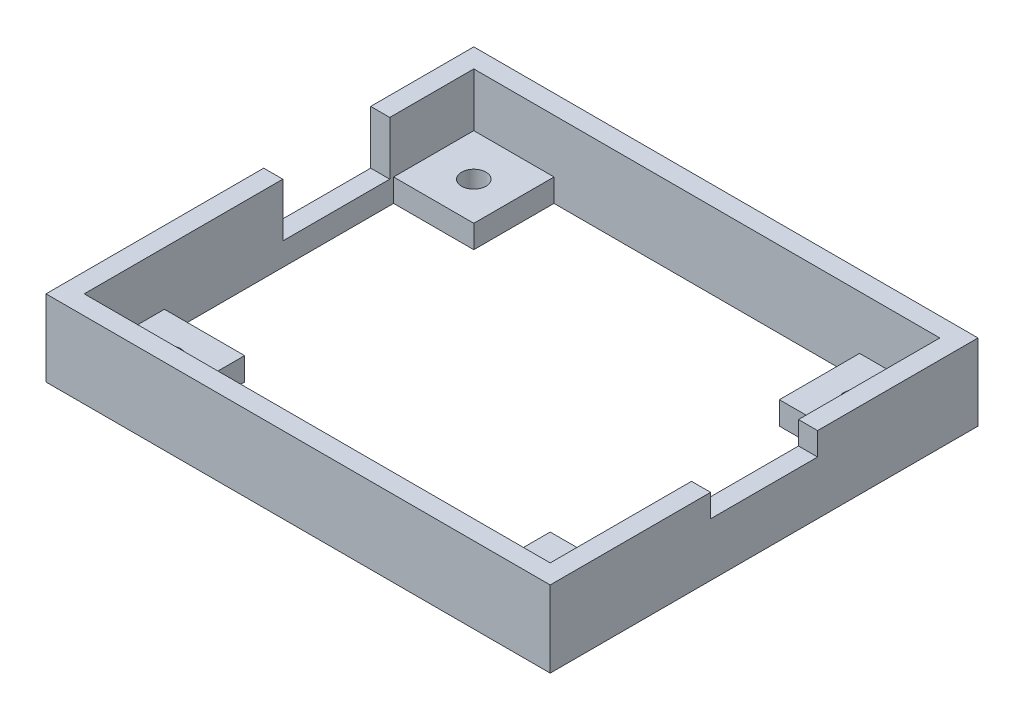
SolidWorks part; units mm, degrees
ref_plane "前视基准面" through (0, 0, 0) normal (0, 0, 1) x (1, 0, 0)
ref_plane "上视基准面" through (0, 0, 0) normal (0, 1, 0) x (1, 0, 0)
ref_plane "右视基准面" through (0, 0, 0) normal (1, 0, 0) x (0, 0, -1)
sketch "草图1" plane through (0, 0, 0) normal (0, 1, 0) x (1, 0, 0)
  line L1 (33, -28) -> (-33, -28)
  line L2 (33, -28) -> (33, 28)
  line L3 (33, 28) -> (-33, 28)
  line L4 (-33, -28) -> (-33, 28)
  line L5 (33, -28) -> (-33, 28) construction
  line L6 (33, 28) -> (-33, -28) construction
  point P0 (0, 0)
  dimension "D1" = 66
  dimension "D2" = 56
extrude "凸台-拉伸1" add sketch "草图1" along normal blind 10
sketch "草图2" plane through (0, 10, 0) normal (0, 1, 0) x (1, 0, 0)
  line L1 (30.5, -25.5) -> (-30.5, -25.5)
  line L2 (30.5, -25.5) -> (30.5, 25.5)
  line L3 (30.5, 25.5) -> (-30.5, 25.5)
  line L4 (-30.5, -25.5) -> (-30.5, 25.5)
  line L5 (30.5, -25.5) -> (-30.5, 25.5) construction
  line L6 (30.5, 25.5) -> (-30.5, -25.5) construction
  point P0 (0, 0)
  dimension "D1" = 61
  dimension "D2" = 51
extrude "切除-拉伸1" cut sketch "草图2" against normal blind 7
sketch "草图3" plane through (0, 3, 0) normal (0, 1, 0) x (1, 0, 0)
  line L1 (25, -20) -> (-25, -20) construction
  line L2 (25, -20) -> (25, 20) construction
  line L3 (25, 20) -> (-25, 20) construction
  line L4 (-25, -20) -> (-25, 20) construction
  line L5 (25, -20) -> (-25, 20) construction
  line L6 (25, 20) -> (-25, -20) construction
  circle A0 centre (-25, 20) radius 1.6
  point P0 (0, 0)
  dimension "D3" = 3.2
  dimension "D1" = 50
  dimension "D2" = 40
extrude "切除-拉伸2" cut sketch "草图3" against normal through all
pattern_linear "阵列(线性)1" count 2 spacing 50 along (1, 0, 0) count 2 spacing 40 along (0, 0, 1) of "切除-拉伸2"
sketch "草图4" plane through (0, 3, 0) normal (0, 1, 0) x (1, 0, 0)
  line L0 (-30.5, 25.5) -> (-30.5, -25.5) construction
  line L1 (30.5, -15) -> (-30.5, -15)
  line L2 (30.5, -15) -> (30.5, 15)
  line L3 (30.5, 15) -> (-30.5, 15)
  line L4 (-30.5, -15) -> (-30.5, 15)
  line L5 (30.5, -15) -> (-30.5, 15) construction
  line L6 (30.5, 15) -> (-30.5, -15) construction
  line L7 (30.5, 25.5) -> (-30.5, 25.5) construction
  line L8 (20, -25.5) -> (-20, -25.5)
  line L9 (20, -25.5) -> (20, 25.5)
  line L10 (20, 25.5) -> (-20, 25.5)
  line L11 (-20, -25.5) -> (-20, 25.5)
  line L12 (20, -25.5) -> (-20, 25.5) construction
  line L13 (20, 25.5) -> (-20, -25.5) construction
  point P0 (0, 0)
  point P8 (0, 0)
  line M8 (-30.5, 25.5) -> (-30.5, -25.5)
  line M9 (-30.5, -25.5) -> (30.5, -25.5)
  line M10 (30.5, -25.5) -> (30.5, 25.5)
  line M11 (30.5, 25.5) -> (-30.5, 25.5)
  dimension "D1" = 30
  dimension "D2" = 40
extrude "切除-拉伸3" cut sketch "草图4" against normal through all contours L11 L3 L9 M11 | L1 L11 L3 M8 | L11 L1 L9 L3 | L11 L9 L1 M9 | L9 L1 L3 M10
sketch "草图6" plane through (-30.5, 0, 0) normal (1, 0, 0) x (0, 0, -1)
  line L0 (25.5, 10) -> (-25.5, 10) construction
  line L1 (0.5, 3) -> (14.5, 3)
  line L2 (0.5, 3) -> (0.5, 10)
  line L3 (0.5, 10) -> (14.5, 10)
  line L4 (14.5, 3) -> (14.5, 10)
  line L5 (28, 10) -> (28, 0) construction
  dimension "D1" = 14
  dimension "D2" = 7
  dimension "D3" = 13.5
extrude "切除-拉伸6" cut sketch "草图6" against normal blind 10 contours L2 L3 L4 L1
sketch "草图7" plane through (33, 0, 0) normal (1, 0, 0) x (0, 0, -1)
  line L0 (-28, 10) -> (28, 10) construction
  line L1 (-7, 10) -> (7, 10)
  line L2 (-7, 10) -> (-7, 7)
  line L3 (-7, 7) -> (7, 7)
  line L4 (7, 10) -> (7, 7)
  line L5 (-28, 10) -> (-28, 0) construction
  dimension "D1" = 14
  dimension "D2" = 3
  dimension "D3" = 21
extrude "切除-拉伸7" cut sketch "草图7" against normal blind 10
